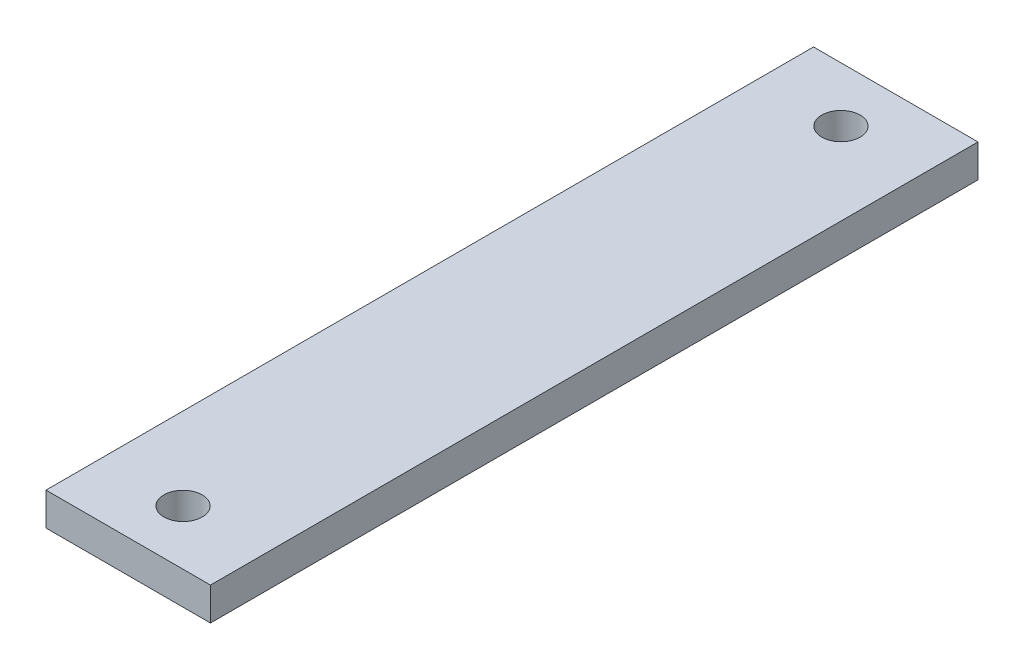
SolidWorks part; units mm, degrees
ref_plane "Front Plane" through (0, 0, 0) normal (0, 0, 1) x (1, 0, 0)
ref_plane "Top Plane" through (0, 0, 0) normal (0, 1, 0) x (1, 0, 0)
ref_plane "Right Plane" through (0, 0, 0) normal (1, 0, 0) x (0, 0, -1)
sketch "Sketch1" plane through (0, 0, 0) normal (0, 1, 0) x (1, 0, 0)
  line L0 (-1219.8412, 35) -> (59772.2193, 35) construction
  line L1 (0, 0) -> (15, 0)
  line L2 (0, 0) -> (0, 70)
  line L3 (0, 70) -> (15, 70)
  line L4 (15, 0) -> (15, 70)
  circle A0 centre (7.5, 5) radius 1.75
  circle A1 centre (7.5, 65) radius 1.75
  point P10 (0, 35)
  point P12 (0, 0)
  point P13 (7.5, 70)
  dimension "D1" = 60
  dimension "D3" = 3.5
  dimension "D2" = 70
  dimension "D4" = 15
extrude "Boss-Extrude1" add sketch "Sketch1" along normal blind 3
